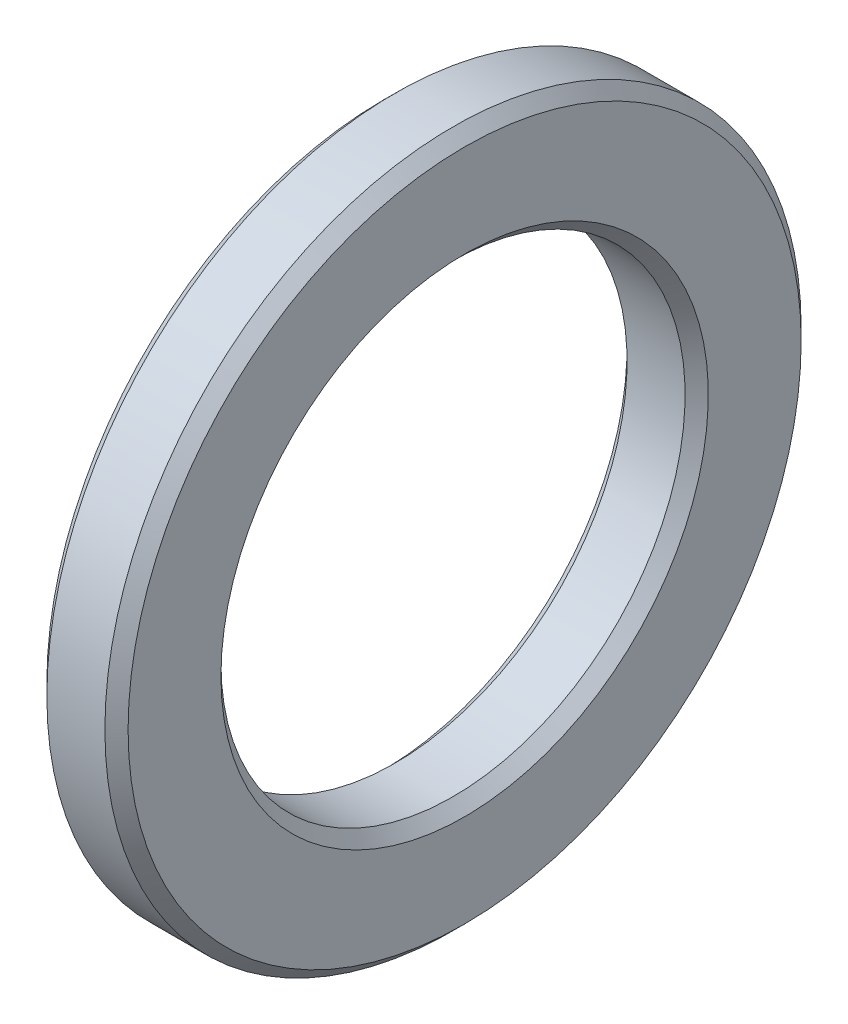
SolidWorks part; units mm, degrees
ref_plane "Plan de face" through (0, 0, 0) normal (0, 0, 1) x (1, 0, 0)
ref_plane "Plan de dessus" through (0, 0, 0) normal (0, 1, 0) x (1, 0, 0)
ref_plane "Plan de droite" through (0, 0, 0) normal (1, 0, 0) x (0, 0, -1)
sketch "Esquisse1" plane through (0, 0, 0) normal (0, 0, 1) x (1, 0, 0)
  line L0 (-15.0831, 0) -> (53.6286, 0) construction
  line L1 (0, 8.7) -> (0.3, 9)
  line L2 (0.3, 6) -> (1.8, 6)
  line L3 (0, 6.3) -> (0, 8.7)
  line L4 (0.3, 9) -> (1.8, 9)
  line L5 (2.1, 6.3) -> (2.1, 8.7)
  line L6 (2.1, 8.7) -> (1.8, 9)
  line L7 (1.8, 6) -> (2.1, 6.3)
  line L8 (0, 6.3) -> (0.3, 6)
  point P3 (0, 6)
  point P4 (2.1, 9)
  point P5 (0, 9)
  point P6 (2.1, 6)
  dimension "D1" = 12
  dimension "D2" = 18
  dimension "D3" = 2.1
  dimension "D6" = 0.3
  dimension "D7" = 0.3
  dimension "D8" = 0.3
  dimension "D9" = 0.3
revolve "Révolution1" add sketch "Esquisse1" angle 360 about L0
